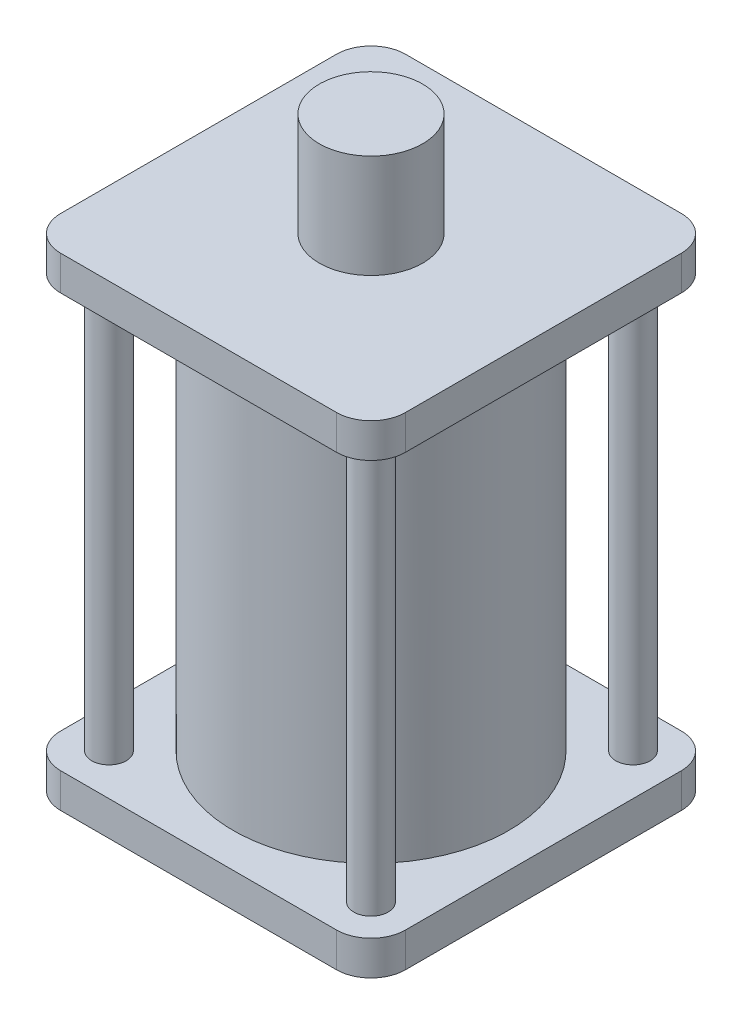
SolidWorks part; units mm, degrees
ref_plane "Front Plane" through (0, 0, 0) normal (0, 0, 1) x (1, 0, 0)
ref_plane "Top Plane" through (0, 0, 0) normal (0, 1, 0) x (1, 0, 0)
ref_plane "Right Plane" through (0, 0, 0) normal (1, 0, 0) x (0, 0, -1)
sketch "Sketch1" plane through (0, 0, 0) normal (0, 1, 0) x (1, 0, 0)
  line L1 (-50, -50) -> (50, -50)
  line L2 (-50, -50) -> (-50, 50)
  line L3 (-50, 50) -> (50, 50)
  line L4 (50, -50) -> (50, 50)
  line L5 (-50, -50) -> (50, 50) construction
  line L6 (-50, 50) -> (50, -50) construction
  point P0 (0, 0)
  dimension "D1" = 100
  dimension "D2" = 100
extrude "Boss-Extrude1" add sketch "Sketch1" along normal blind 10
sketch "Sketch2" plane through (0, 10, 0) normal (0, 1, 0) x (1, 0, 0)
  circle A0 centre (0, 0) radius 40
  dimension "D1" = 80
extrude "Boss-Extrude2" add sketch "Sketch2" along normal blind 120 separate body
sketch "Sketch3" plane through (0, 130, 0) normal (0, 1, 0) x (1, 0, 0)
  line L1 (-50, 50) -> (50, 50)
  line L2 (-50, 50) -> (-50, -50)
  line L3 (-50, -50) -> (50, -50)
  line L4 (50, 50) -> (50, -50)
extrude "Boss-Extrude3" add sketch "Sketch3" along normal blind 10 separate body
sketch "Sketch4" plane through (0, 140, 0) normal (0, 1, 0) x (1, 0, 0)
  circle A0 centre (0, 0) radius 15
  dimension "D1" = 30
extrude "Boss-Extrude4" add sketch "Sketch4" along normal blind 30 separate body
sketch "Sketch5" plane through (0, 10, 0) normal (0, 1, 0) x (1, 0, 0)
  line L0 (-50, 50) -> (-50, -50) construction
  line L1 (50, 50) -> (-50, 50) construction
  line L2 (0, 50) -> (0, 0) construction
  line L3 (0, 0) -> (50, 0) construction
  line L4 (50, -50) -> (50, 50) construction
  circle A0 centre (-38, 38) radius 5
  circle A1 centre (38, 38) radius 5
  circle A2 centre (38, -38) radius 5
  circle A3 centre (-38, -38) radius 5
  dimension "D1" = 10
  dimension "D2" = 12
  dimension "D3" = 12
extrude "Boss-Extrude5" add sketch "Sketch5" along normal up to surface (120 mm away) up to face at (0, 130, 0)
fillet "Fillet1" radius 10 8 edges at (50, 5, -50) (50, 5, 50) (-50, 5, 50) (-50, 5, -50) (-50, 135, -50) (50, 135, -50) (50, 135, 50) (-50, 135, 50)
